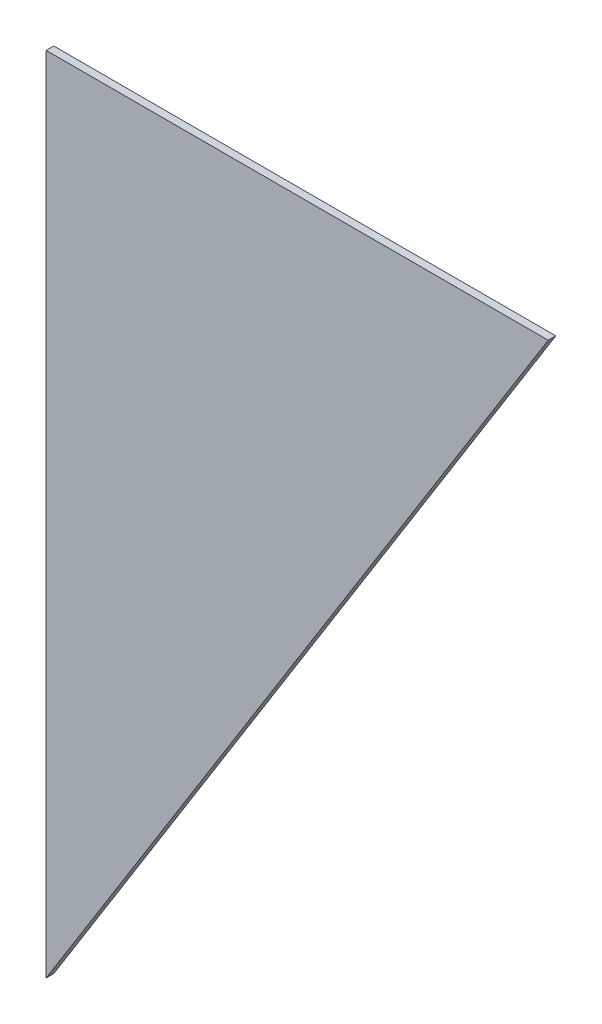
SolidWorks part; units mm, degrees
material "Acrylic (Medium-high impact)"
ref_plane "Front Plane" through (0, 0, 0) normal (0, 0, 1) x (1, 0, 0)
ref_plane "Top Plane" through (0, 0, 0) normal (0, 1, 0) x (1, 0, 0)
ref_plane "Right Plane" through (0, 0, 0) normal (1, 0, 0) x (0, 0, -1)
sketch "Sketch1" plane through (0, 0, 0) normal (0, 0, 1) x (1, 0, 0)
  line L0 (0, -2482.0819) -> (0, 121622.0147) construction
  line L1 (-2482.0819, 0) -> (121622.0147, 0) construction
  line L2 (-200, -320) -> (0, 0)
  line L4 (-200, -320) -> (-200, 0)
  line L5 (-200, 0) -> (0, 0) construction
  line L6 (-200, -3) -> (-1.875, -3)
  dimension "D1" = 320
  dimension "D2" = 200
  dimension "D3" = 3
extrude "Boss-Extrude1" add sketch "Sketch1" along normal blind 3 contours L6 L4 L2
